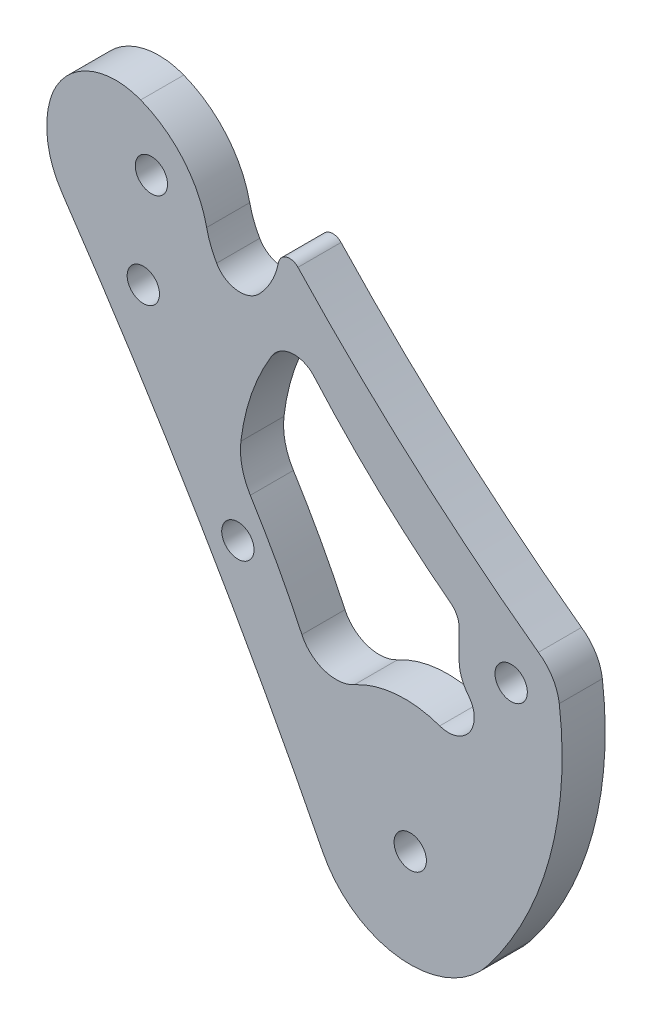
SolidWorks part; units mm, degrees
ref_plane "Plan de face" through (0, 0, 0) normal (0, 0, 1) x (1, 0, 0)
ref_plane "Plan de dessus" through (0, 0, 0) normal (0, 1, 0) x (1, 0, 0)
ref_plane "Plan de droite" through (0, 0, 0) normal (1, 0, 0) x (0, 0, -1)
sketch "Esquisse1" plane through (0, 0, 0) normal (0, 0, 1) x (1, 0, 0)
  line L0 (73.4009, 459.4032) -> (81.5095, 453.5509) construction
  line L1 (96.8497, 30.849) -> (96.8497, 33.4747)
  circle A1 centre (68.2855, 55.5604) radius 1.5
  circle A2 centre (101.6821, 31.4335) radius 1.5
  circle A3 centre (92.3124, 13.2001) radius 1.5
  circle A4 centre (67.5355, 46.3604) radius 1.5011
  arc A6 (60.0269, 49.9216) -> (84.1953, 9.0864) centre (-239.9507, -155.19) cw
  arc A7 (84.1953, 9.0864) -> (99.5091, 7.6308) centre (92.3124, 13.2001) ccw
  arc A8 (99.5091, 7.6308) -> (106.1459, 32.003) centre (73.4112, 27.8273) ccw
  arc A9 (106.1459, 32.003) -> (104.2103, 35.1562) centre (101.6821, 31.4335) ccw
  arc A11 (77.4672, 34.4096) -> (82.254, 25.6053) centre (6.216, -10.033) cw
  arc A12 (82.254, 25.6053) -> (87.1342, 24.0178) centre (85.4377, 27.0974) ccw
  arc A13 (87.1342, 24.0178) -> (95.0512, 24.6624) centre (91.8101, 15.5295) cw
  arc A14 (95.0512, 24.6624) -> (97.7092, 28.4438) centre (95.8535, 26.9233) ccw
  arc A15 (97.7092, 28.4438) -> (96.8497, 30.849) centre (100.6448, 30.849) cw
  arc A16 (96.8497, 33.4747) -> (96.0818, 35.0326) centre (94.8854, 33.4747) ccw
  arc A17 (96.0818, 35.0326) -> (83.3729, 46.9299) centre (150.5127, 105.913) cw
  arc A18 (83.3729, 46.9299) -> (79.4458, 46.5889) centre (81.5348, 45.315) ccw
  arc A19 (79.4458, 46.5889) -> (76.5917, 38.3167) centre (96.9244, 35.93) ccw
  arc A20 (76.5917, 38.3167) -> (77.4672, 34.4096) centre (82.6003, 37.6114) ccw
  arc A21 (74.9462, 53.0521) -> (69.969, 62.4758) centre (68.2855, 55.5604) ccw construction
  arc A22 (77.4672, 52.4638) -> (70.5815, 64.9743) centre (68.2855, 55.5604) ccw construction
  arc A23 (60.0269, 49.9216) -> (58.8919, 56.9478) centre (66.9298, 54.6414) cw
  arc A24 (58.8919, 56.9478) -> (67.2916, 61.1038) centre (64.985, 55.1994) cw
  arc A25 (67.2916, 61.1038) -> (73.413, 53.9091) centre (63.663, 51.8151) cw
  arc A26 (73.413, 53.9091) -> (74.3377, 51.5052) centre (81.5329, 55.653) ccw
  arc A27 (74.3377, 51.5052) -> (78.3015, 51.0166) centre (76.5036, 52.7538) ccw
  arc A28 (78.3015, 51.0166) -> (80.0855, 54.43) centre (73.4029, 55.7497) ccw
  arc A29 (80.0855, 54.43) -> (81.8892, 54.9461) centre (81.1196, 54.2258) cw
  arc A30 (81.8892, 54.9461) -> (104.2103, 35.1562) centre (199.0673, 164.6287) ccw
  dimension "D2" = 3
  dimension "D8" = 2.5
  dimension "D9" = 363.3969
  dimension "D10" = 9.1
  dimension "D11" = 33
  dimension "D12" = 4.5
  dimension "D1" = 10
  dimension "D3" = 41.2
  dimension "D4" = 48.7
  dimension "D5" = 20.5
  dimension "D6" = 9.2
  dimension "D7" = 0.75
extrude "Boss.-Extru.1" add sketch "Esquisse1" along normal blind 4
sketch "Esquisse2" plane through (0, 0, 4) normal (0, 0, 1) x (1, 0, 0)
  circle A0 centre (76.3124, 30.2001) radius 1.5
  circle A1 centre (92.3124, 13.2001) radius 1.5 construction
  dimension "D1" = 17
  dimension "D3" = 3
  dimension "D2" = 16
extrude "Enlèv. mat.-Extru.1" cut sketch "Esquisse2" against normal up to next
